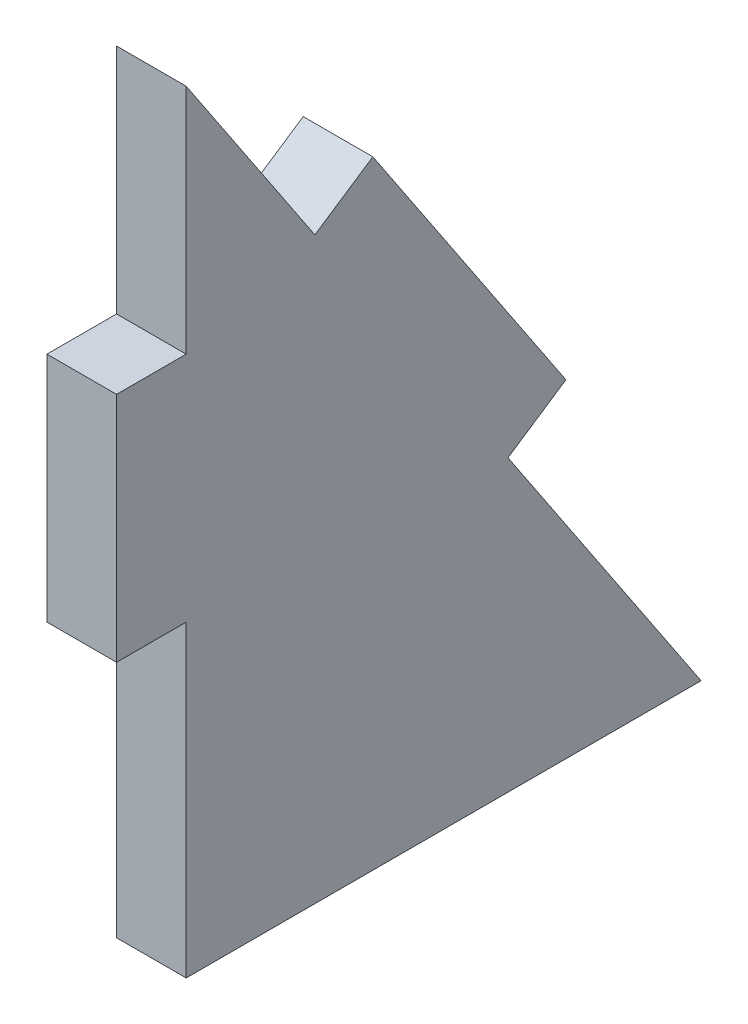
SolidWorks part; units mm, degrees
ref_plane "Front Plane" through (0, 0, 0) normal (0, 0, 1) x (1, 0, 0)
ref_plane "Top Plane" through (0, 0, 0) normal (0, 1, 0) x (1, 0, 0)
ref_plane "Right Plane" through (0, 0, 0) normal (1, 0, 0) x (0, 0, -1)
sketch "Sketch1" plane through (0, 0, 0) normal (1, 0, 0) x (0, 0, -1)
  line L0 (0, 33.282) -> (5.547, 24.9615)
  line L1 (0, 0) -> (22.188, 0)
  line L2 (0, 0) -> (0, 13.282)
  line L4 (0, 23.282) -> (0, 33.282)
  line L5 (0, 23.282) -> (-3, 23.282)
  line L7 (0, 13.282) -> (-3, 13.282)
  line L8 (-3, 23.282) -> (-3, 13.282)
  line L9 (5.547, 24.9615) -> (8.0432, 26.6256)
  line L13 (13.8675, 12.4808) -> (16.3637, 14.1449)
  line L14 (8.0432, 26.6256) -> (16.3637, 14.1449)
  line L15 (13.8675, 12.4808) -> (22.188, 0)
  dimension "D2" = 40
  dimension "D3" = 10
  dimension "D4" = 10
  dimension "D5" = 10
  dimension "D6" = 3
  dimension "D7" = 56.31
  dimension "D8" = 90
  dimension "D9" = 15
  dimension "D10" = 3
  dimension "D12" = 90
  dimension "D13" = 90
  dimension "D14" = 90
extrude "Boss-Extrude1" add sketch "Sketch1" along normal blind 3
